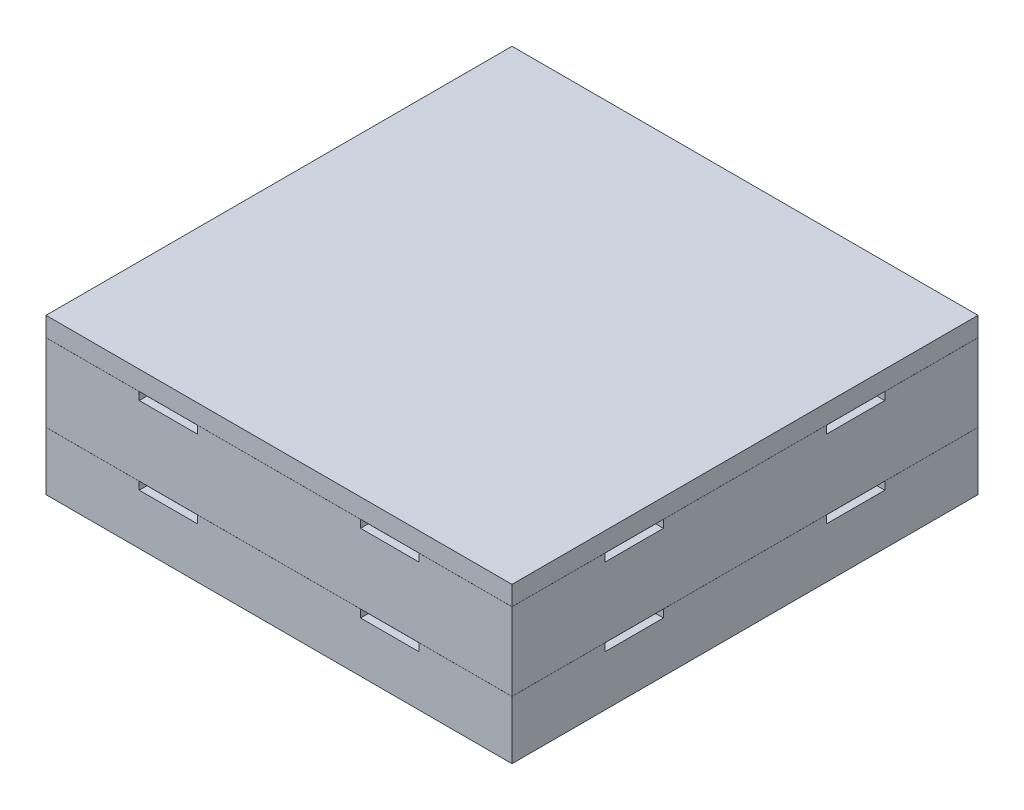
SolidWorks part; units mm, degrees
ref_plane "前视基准面" through (0, 0, 0) normal (0, 0, 1) x (1, 0, 0)
ref_plane "上视基准面" through (0, 0, 0) normal (0, 1, 0) x (1, 0, 0)
ref_plane "右视基准面" through (0, 0, 0) normal (1, 0, 0) x (0, 0, -1)
other "Configuration Table"
sketch "草图1" plane through (0, 0, 0) normal (0, 1, 0) x (1, 0, 0)
  line L5 (0, 0) -> (-600, 0)
  line L6 (0, 0) -> (0, -600)
  line L7 (0, -600) -> (-600, -600)
  line L8 (-600, 0) -> (-600, -600)
  dimension "D1" = 600
extrude "凸台-拉伸1" add sketch "草图1" along normal blind 400
sketch "草图2" plane through (-600, 0, 0) normal (-1, 0, 0) x (0, 0, 1)
  line L0 (600, 150.2) -> (0, 150.2)
  line L1 (600, 400) -> (600, 0) construction
  line L2 (0, 400) -> (0, 0) construction
  line L3 (0, 150.2) -> (0, 150)
  line L4 (0, 150) -> (210, 150)
  line L5 (210, 150) -> (210, 130)
  line L6 (210, 130) -> (360, 130)
  line L7 (360, 130) -> (360, 150)
  line L8 (360, 150) -> (600, 150)
  line L13 (600, 150) -> (600, 150.2)
  line L14 (0, 0) -> (600, 0) construction
  dimension "D1" = 0.2
  dimension "D2" = 20
  dimension "D3" = 150
  dimension "D4" = 240
  dimension "D5" = 210
  dimension "D6" = 150
extrude "切除-拉伸1" cut sketch "草图2" against normal blind 20
sketch "草图3" plane through (0, 0, 600) normal (0, 0, 1) x (1, 0, 0)
  line L0 (-580, 150.2) -> (-580, 150)
  line L1 (-580, 150) -> (-360, 150)
  line L2 (-360, 150) -> (-360, 130)
  line L3 (-360, 130) -> (-210, 130)
  line L4 (-210, 130) -> (-210, 150)
  line L5 (-210, 150) -> (0, 150)
  line L6 (0, 400) -> (0, 0) construction
  line L7 (0, 150) -> (0, 150.2)
  line L8 (0, 150.2) -> (-580, 150.2)
  line L9 (-600, 150) -> (-600, 0) construction
  dimension "D1" = 20
  dimension "D2" = 150
  dimension "D3" = 240
extrude "切除-拉伸2" cut sketch "草图3" against normal blind 20
pattern_linear "阵列(线性)1" count 2 spacing 200 along (0, 1, 0) of "切除-拉伸1", "切除-拉伸2"
mirror "镜向1" about plane through (0, 400, 0) normal (0, 0, 1) of bodies 111 108
mirror "镜向2" about plane through (0, 400, 0) normal (-1, 0, 0) of bodies 109
